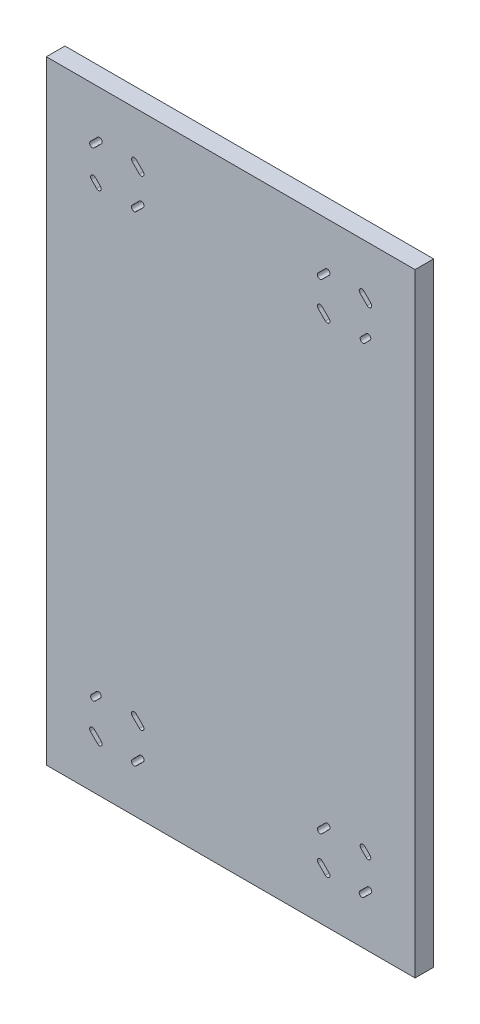
SolidWorks part; units mm, degrees
material "Balsa"
ref_plane "Front Plane" through (0, 0, 0) normal (0, 0, 1) x (1, 0, 0)
ref_plane "Top Plane" through (0, 0, 0) normal (0, 1, 0) x (1, 0, 0)
ref_plane "Right Plane" through (0, 0, 0) normal (1, 0, 0) x (0, 0, -1)
sketch "Sketch1" plane through (0, 0, 0) normal (0, 0, 1) x (1, 0, 0)
  line L1 (-377.825, 628.65) -> (377.825, 628.65)
  line L2 (-377.825, 628.65) -> (-377.825, -628.65)
  line L3 (-377.825, -628.65) -> (377.825, -628.65)
  line L4 (377.825, 628.65) -> (377.825, -628.65)
  line L5 (-377.825, 628.65) -> (377.825, -628.65) construction
  line L6 (-377.825, -628.65) -> (377.825, 628.65) construction
  point P0 (0, 0)
  dimension "D1" = 755.65
  dimension "D2" = 1257.3
extrude "Boss-Extrude1" add sketch "Sketch1" along normal blind 38.1 contours L2 L1 L4 L3
sketch "Sketch2" plane through (0, 628.65, 0) normal (0, 1, 0) x (1, 0, 0)
  line L0 (377.825, -38.1) -> (377.825, 0) construction
  line L1 (-377.825, 0) -> (377.825, 0) construction
  line L2 (-377.825, -38.1) -> (377.825, -38.1) construction
  point P0 (365.125, -6.35)
  point P1 (365.125, -31.75)
  dimension "D1" = 12.7
  dimension "D2" = 6.35
  dimension "D3" = 12.7
  dimension "D4" = 6.35
sketch "Sketch3" plane through (0, 628.65, 0) normal (0, 1, 0) x (1, 0, 0)
  line L0 (-377.825, 0) -> (377.825, 0) construction
  line L1 (-377.825, -38.1) -> (-377.825, 0) construction
  line L2 (-377.825, -38.1) -> (377.825, -38.1) construction
  point P0 (-365.125, -6.35)
  point P1 (-365.125, -31.75)
  dimension "D1" = 6.35
  dimension "D2" = 12.7
  dimension "D3" = 6.35
  dimension "D4" = 12.7
sketch "Sketch6" plane through (0, 0, 38.1) normal (0, 0, 1) x (1, 0, 0)
  line L0 (0, -628.65) -> (0, 628.65) construction
  line L3 (-377.825, 628.65) -> (377.825, 628.65) construction
  line L12 (377.825, 0) -> (-377.825, 0) construction
  line L15 (-377.825, 628.65) -> (-377.825, -628.65) construction
  line L20 (377.825, 628.65) -> (377.825, -628.65) construction
  line L22 (283.5215, -519.7535) -> (268.9285, -534.3465) construction
  line L25 (287.4503, -523.6824) -> (272.8574, -538.2753)
  line L28 (279.5926, -515.8247) -> (264.9997, -530.4176)
  line L31 (197.7965, -534.3465) -> (183.2035, -519.7535) construction
  line L34 (-283.5215, -519.7535) -> (-268.9285, -534.3465) construction
  line L37 (-287.4503, -523.6824) -> (-272.8574, -538.2753)
  line L40 (-279.5926, -515.8247) -> (-264.9997, -530.4176)
  line L43 (-197.7965, -534.3465) -> (-183.2035, -519.7535) construction
  line L46 (-193.8676, -538.2753) -> (-179.2747, -523.6824)
  line L49 (-201.7253, -530.4176) -> (-187.1324, -515.8247)
  line L52 (-270.893, -450.2805) -> (-281.557, -460.9445) construction
  line L55 (-274.8218, -446.3516) -> (-285.4859, -457.0157)
  line L58 (-377.825, -628.65) -> (377.825, -628.65) construction
  line L60 (193.8676, -538.2753) -> (179.2747, -523.6824)
  line L61 (201.7253, -530.4176) -> (187.1324, -515.8247)
  line L62 (270.893, -450.2805) -> (281.557, -460.9445) construction
  line L63 (274.8218, -446.3516) -> (285.4859, -457.0157)
  line L64 (266.9641, -454.2093) -> (277.6282, -464.8734)
  line L65 (197.7965, -449.4686) -> (183.2035, -464.0615) construction
  line L66 (201.7253, -453.3974) -> (187.1324, -467.9904)
  line L67 (193.8676, -445.5397) -> (179.2747, -460.1326)
  line L68 (-266.9641, -454.2093) -> (-277.6282, -464.8734)
  line L69 (-197.7965, -449.4686) -> (-183.2035, -464.0615) construction
  line L70 (-201.7253, -453.3974) -> (-187.1324, -467.9904)
  line L71 (-193.8676, -445.5397) -> (-179.2747, -460.1326)
  line L72 (283.5215, 519.7535) -> (268.9285, 534.3465) construction
  line L73 (287.4503, 523.6824) -> (272.8574, 538.2753)
  line L74 (279.5926, 515.8247) -> (264.9997, 530.4176)
  line L75 (197.7965, 534.3465) -> (183.2035, 519.7535) construction
  line L76 (193.8676, 538.2753) -> (179.2747, 523.6824)
  line L77 (201.7253, 530.4176) -> (187.1324, 515.8247)
  line L78 (-283.5215, 519.7535) -> (-268.9285, 534.3465) construction
  line L79 (-287.4503, 523.6824) -> (-272.8574, 538.2753)
  line L80 (-279.5926, 515.8247) -> (-264.9997, 530.4176)
  line L81 (-197.7965, 534.3465) -> (-183.2035, 519.7535) construction
  line L82 (-193.8676, 538.2753) -> (-179.2747, 523.6824)
  line L83 (-201.7253, 530.4176) -> (-187.1324, 515.8247)
  line L84 (-270.893, 450.2805) -> (-281.557, 460.9445) construction
  line L85 (-274.8218, 446.3516) -> (-285.4859, 457.0157)
  line L86 (-266.9641, 454.2093) -> (-277.6282, 464.8734)
  line L87 (270.893, 450.2805) -> (281.557, 460.9445) construction
  line L88 (274.8218, 446.3516) -> (285.4859, 457.0157)
  line L89 (266.9641, 454.2093) -> (277.6282, 464.8734)
  line L90 (197.7965, 449.4686) -> (183.2035, 464.0615) construction
  line L91 (201.7253, 453.3974) -> (187.1324, 467.9904)
  line L92 (193.8676, 445.5397) -> (179.2747, 460.1326)
  line L93 (-197.7965, 449.4686) -> (-183.2035, 464.0615) construction
  line L94 (-201.7253, 453.3974) -> (-187.1324, 467.9904)
  line L95 (-193.8676, 445.5397) -> (-179.2747, 460.1326)
  arc A40 (287.4503, -523.6824) -> (279.5926, -515.8247) centre (283.5215, -519.7535) ccw
  arc A41 (264.9997, -530.4176) -> (272.8574, -538.2753) centre (268.9285, -534.3465) ccw
  arc A42 (193.8676, -538.2753) -> (201.7253, -530.4176) centre (197.7965, -534.3465) ccw
  arc A43 (187.1324, -515.8247) -> (179.2747, -523.6824) centre (183.2035, -519.7535) ccw
  arc A44 (274.8218, -446.3516) -> (266.9641, -454.2093) centre (270.893, -450.2805) ccw
  arc A45 (277.6282, -464.8734) -> (285.4859, -457.0157) centre (281.557, -460.9445) ccw
  arc A46 (201.7253, -453.3974) -> (193.8676, -445.5397) centre (197.7965, -449.4686) ccw
  arc A47 (179.2747, -460.1326) -> (187.1324, -467.9904) centre (183.2035, -464.0615) ccw
  arc A48 (-287.4503, -523.6824) -> (-279.5926, -515.8247) centre (-283.5215, -519.7535) cw
  arc A49 (-264.9997, -530.4176) -> (-272.8574, -538.2753) centre (-268.9285, -534.3465) cw
  arc A50 (-193.8676, -538.2753) -> (-201.7253, -530.4176) centre (-197.7965, -534.3465) cw
  arc A51 (-187.1324, -515.8247) -> (-179.2747, -523.6824) centre (-183.2035, -519.7535) cw
  arc A52 (-274.8218, -446.3516) -> (-266.9641, -454.2093) centre (-270.893, -450.2805) cw
  arc A53 (-277.6282, -464.8734) -> (-285.4859, -457.0157) centre (-281.557, -460.9445) cw
  arc A54 (-201.7253, -453.3974) -> (-193.8676, -445.5397) centre (-197.7965, -449.4686) cw
  arc A55 (-179.2747, -460.1326) -> (-187.1324, -467.9904) centre (-183.2035, -464.0615) cw
  arc A56 (287.4503, 523.6824) -> (279.5926, 515.8247) centre (283.5215, 519.7535) cw
  arc A57 (264.9997, 530.4176) -> (272.8574, 538.2753) centre (268.9285, 534.3465) cw
  arc A58 (193.8676, 538.2753) -> (201.7253, 530.4176) centre (197.7965, 534.3465) cw
  arc A59 (187.1324, 515.8247) -> (179.2747, 523.6824) centre (183.2035, 519.7535) cw
  arc A60 (-287.4503, 523.6824) -> (-279.5926, 515.8247) centre (-283.5215, 519.7535) ccw
  arc A61 (-264.9997, 530.4176) -> (-272.8574, 538.2753) centre (-268.9285, 534.3465) ccw
  arc A62 (-193.8676, 538.2753) -> (-201.7253, 530.4176) centre (-197.7965, 534.3465) ccw
  arc A63 (-187.1324, 515.8247) -> (-179.2747, 523.6824) centre (-183.2035, 519.7535) ccw
  arc A64 (-274.8218, 446.3516) -> (-266.9641, 454.2093) centre (-270.893, 450.2805) ccw
  arc A65 (-277.6282, 464.8734) -> (-285.4859, 457.0157) centre (-281.557, 460.9445) ccw
  arc A66 (274.8218, 446.3516) -> (266.9641, 454.2093) centre (270.893, 450.2805) cw
  arc A67 (277.6282, 464.8734) -> (285.4859, 457.0157) centre (281.557, 460.9445) cw
  arc A68 (201.7253, 453.3974) -> (193.8676, 445.5397) centre (197.7965, 449.4686) cw
  arc A69 (179.2747, 460.1326) -> (187.1324, 467.9904) centre (183.2035, 464.0615) cw
  arc A70 (-201.7253, 453.3974) -> (-193.8676, 445.5397) centre (-197.7965, 449.4686) ccw
  arc A71 (-179.2747, 460.1326) -> (-187.1324, 467.9904) centre (-183.2035, 464.0615) ccw
  point P10 (-276.225, -527.05)
  point P17 (-190.5, -527.05)
  point P24 (-276.225, -455.6125)
  point P34 (276.225, -527.05)
  point P39 (190.5, -527.05)
  point P46 (276.225, -455.6125)
  point P53 (190.5, -456.765)
  point P60 (285.4859, -464.8734)
  point P62 (-190.5, -456.765)
  point P69 (276.225, 527.05)
  point P76 (190.5, 527.05)
  point P83 (-276.225, 527.05)
  point P90 (-190.5, 527.05)
  point P97 (-276.225, 455.6125)
  point P104 (276.225, 455.6125)
  point P111 (190.5, 456.765)
  point P120 (-190.5, 456.765)
  dimension "D18" = 20.6375
  dimension "D22" = 20.6375
  dimension "D24" = 20.6375
  dimension "D26" = 70.285
  dimension "D20" = 20.6375
  dimension "D17" = 11.1125
  dimension "D19" = 11.1125
  dimension "D21" = 11.1125
  dimension "D23" = 11.1125
  dimension "D25" = 71.4375
  dimension "D27" = 85.725
  dimension "D50" = 85.725
  dimension "D51" = 45
  dimension "D52" = 45
  dimension "D53" = 101.6
  dimension "D54" = 101.6
extrude "Cut-Extrude3" cut sketch "Sketch6" against normal through all
